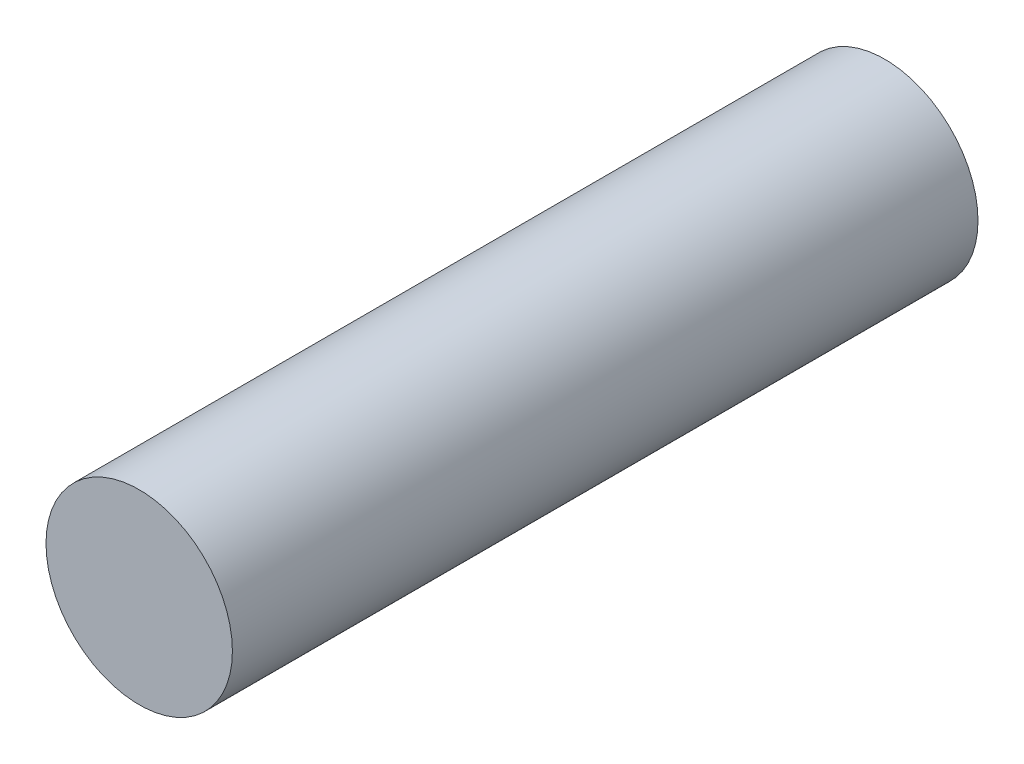
SolidWorks part; units mm, degrees
material "Plain Carbon Steel"
ref_plane "Front Plane" through (0, 0, 0) normal (0, 0, 1) x (1, 0, 0)
ref_plane "Top Plane" through (0, 0, 0) normal (0, 1, 0) x (1, 0, 0)
ref_plane "Right Plane" through (0, 0, 0) normal (1, 0, 0) x (0, 0, -1)
sketch "Sketch1" plane through (0, 0, 0) normal (0, 0, 1) x (1, 0, 0)
  circle A0 centre (0, 0) radius 3.175
  dimension "D1" = 6.35
extrude "Extrude1" add sketch "Sketch1" along normal blind 25.4
